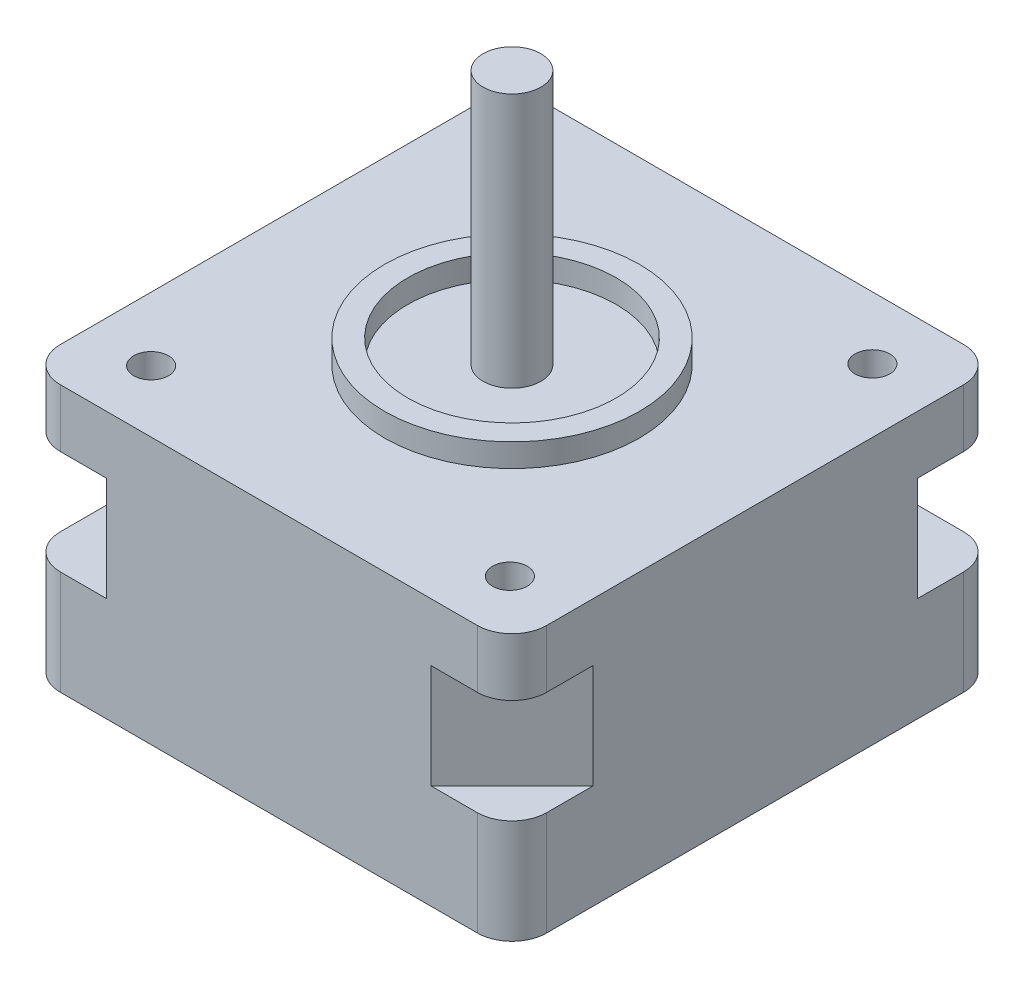
SolidWorks part; units mm, degrees
ref_plane "Front Plane" through (0, 0, 0) normal (0, 0, 1) x (1, 0, 0)
ref_plane "Top Plane" through (0, 0, 0) normal (0, 1, 0) x (1, 0, 0)
ref_plane "Right Plane" through (0, 0, 0) normal (1, 0, 0) x (0, 0, -1)
sketch "Sketch2" plane through (0, 0, 0) normal (0, 1, 0) x (1, 0, 0)
  line L1 (-18, 21) -> (18, 21)
  line L2 (-21, 18) -> (-21, -18)
  line L3 (-18, -21) -> (18, -21)
  line L4 (21, 18) -> (21, -18)
  line L5 (-21, 21) -> (21, -21) construction
  line L6 (-21, -21) -> (21, 21) construction
  arc A0 (-18, -21) -> (-21, -18) centre (-18, -18) cw
  arc A1 (18, -21) -> (21, -18) centre (18, -18) ccw
  arc A2 (18, 21) -> (21, 18) centre (18, 18) cw
  arc A3 (-21, 18) -> (-18, 21) centre (-18, 18) cw
  point P0 (0, 0)
  dimension "D3" = 3
  dimension "D1" = 42
  dimension "D2" = 42
extrude "Boss-Extrude1" add sketch "Sketch2" along normal blind 9
sketch "Sketch3" plane through (0, 9, 0) normal (0, 1, 0) x (1, 0, 0)
  line L0 (-21, 14) -> (-14, 21)
  line L1 (-14, 21) -> (14, 21)
  line L2 (-21, 14) -> (-21, -14)
  line L3 (-14, -21) -> (14, -21)
  line L4 (21, 14) -> (21, -14)
  line L5 (-21, 21) -> (21, -21) construction
  line L6 (-21, -21) -> (21, 21) construction
  line L7 (14, 21) -> (21, 14)
  line L8 (21, -14) -> (14, -21)
  line L9 (-21, -14) -> (-14, -21)
  point P0 (0, 0)
extrude "Boss-Extrude2" add sketch "Sketch3" along normal blind 9
sketch "Sketch4" plane through (0, 18, 0) normal (0, 1, 0) x (1, 0, 0)
  line L1 (-18, 21) -> (18, 21)
  line L2 (-21, 18) -> (-21, -18)
  line L3 (-18, -21) -> (18, -21)
  line L4 (21, 18) -> (21, -18)
  line L5 (-21, 21) -> (21, -21) construction
  line L6 (-21, -21) -> (21, 21) construction
  arc A0 (21, 18) -> (18, 21) centre (18, 18) ccw
  arc A1 (18, -21) -> (21, -18) centre (18, -18) ccw
  arc A2 (-18, -21) -> (-21, -18) centre (-18, -18) cw
  arc A3 (-21, 18) -> (-18, 21) centre (-18, 18) cw
  point P0 (0, 0)
  dimension "D3" = 3
  dimension "D1" = 42
  dimension "D2" = 42
extrude "Boss-Extrude3" add sketch "Sketch4" along normal blind 5
sketch "Sketch5" plane through (0, 23, 0) normal (0, 1, 0) x (1, 0, 0)
  circle A0 centre (0, 0) radius 11
  circle A1 centre (0, 0) radius 9
  dimension "D1" = 22
  dimension "D2" = 18
extrude "Boss-Extrude4" add sketch "Sketch5" along normal blind 2
sketch "Sketch6" plane through (0, 23, 0) normal (0, 1, 0) x (1, 0, 0)
  circle A0 centre (0, 0) radius 2.5
  dimension "D1" = 5
extrude "Boss-Extrude5" add sketch "Sketch6" along normal blind 22
sketch "Sketch7" plane through (0, 23, 0) normal (0, 1, 0) x (1, 0, 0)
  line L1 (-15.5, -15.5) -> (15.5, -15.5) construction
  line L2 (-15.5, -15.5) -> (-15.5, 15.5) construction
  line L3 (-15.5, 15.5) -> (15.5, 15.5) construction
  line L4 (15.5, -15.5) -> (15.5, 15.5) construction
  line L5 (-15.5, -15.5) -> (15.5, 15.5) construction
  line L6 (-15.5, 15.5) -> (15.5, -15.5) construction
  circle A0 centre (-15.5, 15.5) radius 1.5
  circle A1 centre (15.5056, 15.6114) radius 1.5
  circle A2 centre (15.7326, -15.9129) radius 1.5
  circle A3 centre (-15.4949, -15.6632) radius 1.5
  point P0 (0, 0)
  dimension "D3" = 3
  dimension "D1" = 31
  dimension "D2" = 31
extrude "Cut-Extrude1" cut sketch "Sketch7" against normal blind 4.5
sketch "Sketch9" plane through (0, 0, -21) normal (0, 0, -1) x (-1, 0, 0)
  line L1 (-7.5, 9) -> (7.5, 9)
  line L2 (-7.5, 9) -> (-7.5, 4)
  line L3 (-7.5, 4) -> (7.5, 4)
  line L4 (7.5, 9) -> (7.5, 4)
  line L5 (-7.5, 9) -> (7.5, 4) construction
  line L6 (-7.5, 4) -> (7.5, 9) construction
  line L7 (14, 9) -> (18, 9) construction
  line L8 (-18, 0) -> (18, 0) construction
  point P0 (0, 6.5)
  point P10 (0, 0)
  dimension "D1" = 15
  dimension "D2" = 5
extrude "Boss-Extrude6" add sketch "Sketch9" along normal blind 5
